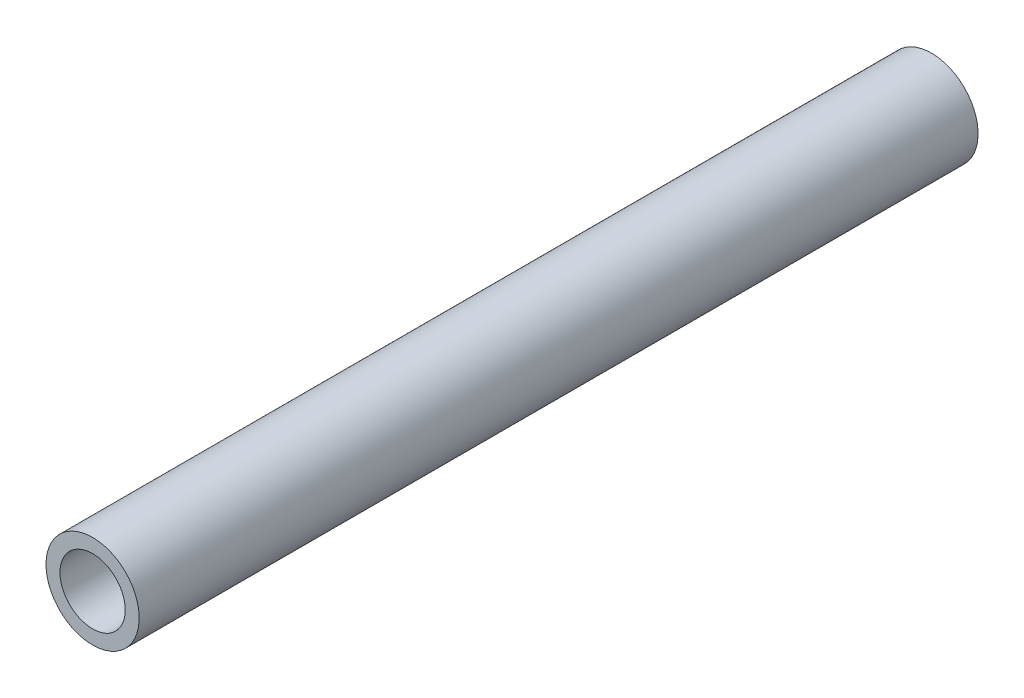
SolidWorks part; units mm, degrees
ref_plane "Front Plane" through (0, 0, 0) normal (0, 0, 1) x (1, 0, 0)
ref_plane "Top Plane" through (0, 0, 0) normal (0, 1, 0) x (1, 0, 0)
ref_plane "Right Plane" through (0, 0, 0) normal (1, 0, 0) x (0, 0, -1)
sketch "Sketch1" plane through (0, 0, 0) normal (0, 0, 1) x (1, 0, 0)
  circle A0 centre (0, 0) radius 5
  circle A1 centre (0, 0) radius 3.5
  dimension "D1" = 10
  dimension "D2" = 7
extrude "Boss-Extrude1" add sketch "Sketch1" along normal blind 90
